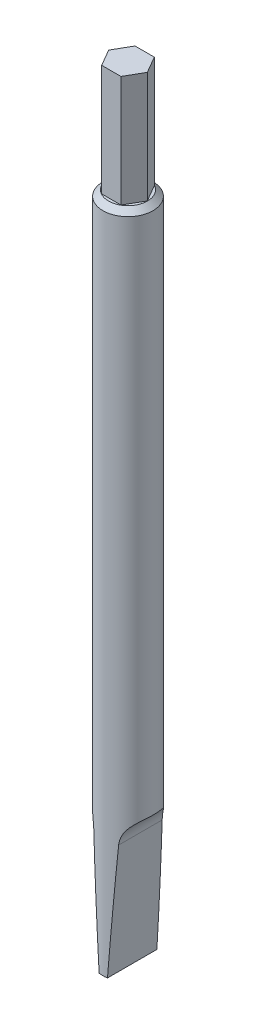
SolidWorks part; units mm, degrees
ref_plane "Front Plane" through (0, 0, 0) normal (0, 0, 1) x (1, 0, 0)
ref_plane "Top Plane" through (0, 0, 0) normal (0, 1, 0) x (1, 0, 0)
ref_plane "Right Plane" through (0, 0, 0) normal (1, 0, 0) x (0, 0, -1)
sketch "Sketch1" plane through (0, 0, 0) normal (0, 1, 0) x (1, 0, 0)
  line L1 (3.4641, 0) -> (1.7321, 3)
  line L2 (1.7321, 3) -> (-1.7321, 3)
  line L3 (-1.7321, 3) -> (-3.4641, 0)
  line L4 (-3.4641, 0) -> (-1.7321, -3)
  line L5 (-1.7321, -3) -> (1.7321, -3)
  line L6 (1.7321, -3) -> (3.4641, 0)
  circle A0 centre (0, 0) radius 3 construction
  point P1 (0, -3)
  dimension "D1" = 6
extrude "Boss-Extrude1" add sketch "Sketch1" along normal blind 20
sketch "Sketch2" plane through (0, 0, 0) normal (0, 1, 0) x (1, 0, 0)
  circle A0 centre (0, 0) radius 4.5
  dimension "D1" = 9
extrude "Boss-Extrude2" add sketch "Sketch2" against normal blind 120
chamfer "Chamfer1" distance 1 angle 45 1 edges at (0, 0, 4.5)
sketch "Sketch4" plane through (0, 0, 3) normal (0, 0, 1) x (1, 0, 0)
  line L0 (-0.75, -120) -> (0.75, -120)
  line L1 (0, 12.3121) -> (0, -12.3121) construction
  line L2 (-4.5, -120) -> (4.5, -120) construction
  line L3 (0.75, -120) -> (2.229, -98.8487)
  line L7 (0, -120) -> (4.5, -120)
  line L8 (4.5, -120) -> (4.5, -95)
  arc A0 (4.5, -95) -> (2.229, -98.8487) centre (7.2169, -99.1975) ccw
  point P6 (0, 0)
  point P8 (0, -120)
  point P13 (0, 0)
  point P14 (0, 0)
  dimension "D3" = 4
  dimension "D4" = 5
  dimension "D1" = 1.5
  dimension "D2" = 4.5
  dimension "D5" = 25
extrude "Cut-Extrude1" cut sketch "Sketch4" against normal mid plane 20 contours L8 A0 L3 L7
mirror "Mirror1" about plane through (0, 0, 0) normal (1, 0, 0) of "Cut-Extrude1"
